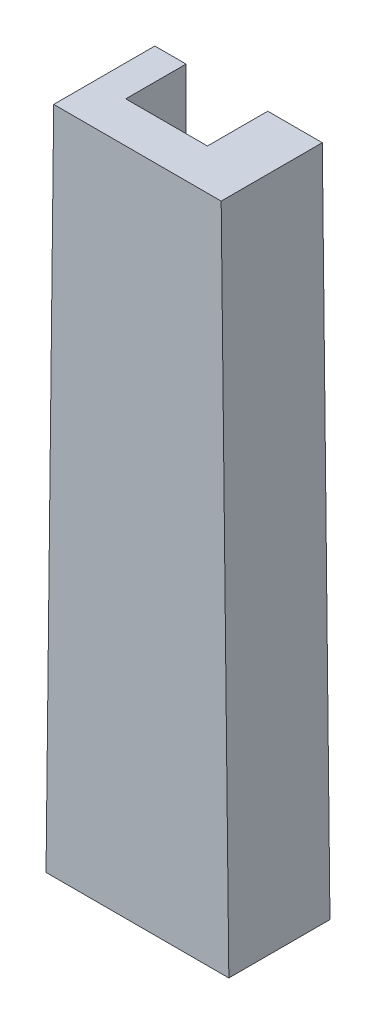
SolidWorks part; units mm, degrees
ref_plane "Front Plane" through (0, 0, 0) normal (0, 0, 1) x (1, 0, 0)
ref_plane "Top Plane" through (0, 0, 0) normal (0, 1, 0) x (1, 0, 0)
ref_plane "Right Plane" through (0, 0, 0) normal (1, 0, 0) x (0, 0, -1)
sketch "Sketch1" plane through (0, 0, 0) normal (0, 1, 0) x (1, 0, 0)
  line L0 (-11.8883, -12.6165) -> (11.6117, -12.6165)
  line L1 (11.6117, -12.6165) -> (11.6117, 0.3835)
  line L2 (11.6117, 0.3835) -> (-11.8883, 0.3835)
  line L3 (-11.8883, 0.3835) -> (-11.8883, -12.6165)
  dimension "D1" = 23.5
  dimension "D2" = 13
ref_plane "Plane1" through (0, 86, 0) normal (0, 1, 0) x (1, 0, 0)
sketch "Sketch2" plane through (0, 86, 0) normal (0, 1, 0) x (1, 0, 0)
  line L2 (-10.9033, -12.6165) -> (-10.9033, 0.3835)
  line L3 (-11.8883, -12.6165) -> (11.6117, -12.6165) construction
  line L4 (11.6117, 0.3835) -> (-11.8883, 0.3835) construction
  line L5 (-10.9033, 0.3835) -> (10.6267, 0.3835)
  line L6 (10.6267, 0.3835) -> (10.6267, -12.6165)
  line L7 (10.6267, -12.6165) -> (-10.9033, -12.6165)
  line L8 (11.6117, -12.6165) -> (11.6117, 0.3835) construction
  dimension "D2" = 0.985
  dimension "D1" = 21.53
loft "Loft1" add profiles "Sketch1", "Sketch2"
sketch "Sketch3" plane through (0, 86, 0) normal (0, 1, 0) x (1, 0, 0)
  line L0 (-6.8883, 0.3835) -> (-6.8883, -7.3693)
  line L1 (10.6267, 0.3835) -> (-10.9033, 0.3835) construction
  line L2 (-6.8883, -7.3693) -> (3.6117, -7.3693)
  line L3 (3.6117, -7.3693) -> (3.6117, 0.3835)
  line L4 (3.6117, 0.3835) -> (-6.8883, 0.3835)
  line L5 (-11.8883, 0.3835) -> (-11.8883, -12.6165) construction
  dimension "D1" = 5
  dimension "D2" = 10.5
extrude "Cut-Extrude1" cut sketch "Sketch3" against normal blind 83
